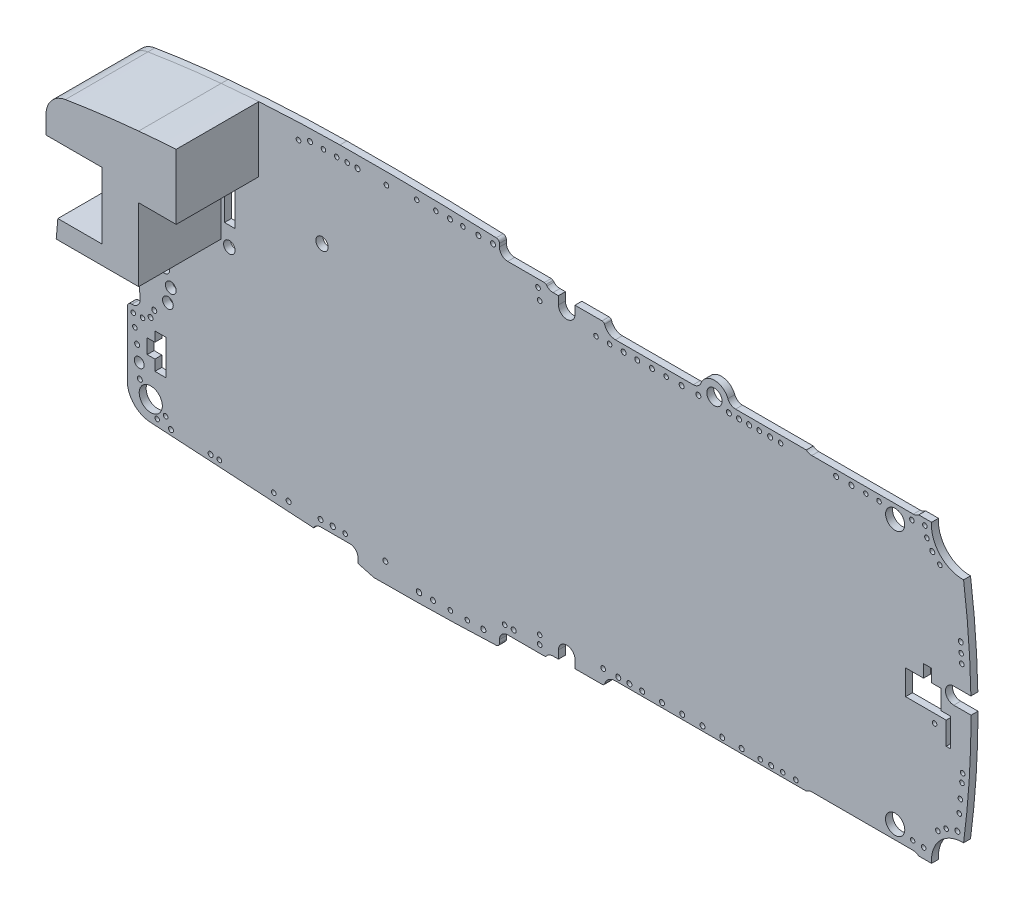
SolidWorks part; units mm, degrees
ref_plane "前视基准面" through (0, 0, 0) normal (0, 0, 1) x (1, 0, 0)
ref_plane "上视基准面" through (0, 0, 0) normal (0, 1, 0) x (1, 0, 0)
ref_plane "右视基准面" through (0, 0, 0) normal (1, 0, 0) x (0, 0, -1)
ref_plane "Dielectric_Layer 图层 1" through (0, 0, 0.84) normal (0, 0, 1) x (1, 0, 0)
sketch "草图1" plane through (0, 0, 0) normal (0, 0, 1) x (1, 0, 0)
  line L0 (-0.5724, -18.938) -> (19.2406, -20.1239)
  line L1 (20.12, -19.6) -> (23.62, -19.6)
  line L2 (24.62, -20.6) -> (24.62, -21.175)
  line L3 (24.62, -21.175) -> (26.5359, -21.6884)
  line L4 (41.75, -20.9855) -> (41.75, -20.6)
  line L5 (42.75, -19.6) -> (47.1862, -19.6)
  line L6 (47.405, -19.5053) -> (47.513, -19.3901)
  line L7 (48.2423, -19.0742) -> (48.9036, -19.0742)
  line L8 (48.9036, -19.0742) -> (48.9034, -18.1002)
  line L9 (50.9034, -18.0998) -> (50.9036, -19.0742)
  line L10 (50.9036, -19.0742) -> (54.2041, -19.0742)
  line L11 (55.8025, -17.9) -> (78.9386, -17.9)
  line L12 (79.6, -17.65) -> (91.9, -17.65)
  line L13 (92.5614, -17.9) -> (94.1119, -17.9)
  line L14 (98.9, 0.05) -> (96.8, 0.05)
  line L15 (96.8, 2.05) -> (98.8801, 2.05)
  line L16 (94.1119, 17.9) -> (92.5614, 17.9)
  line L17 (91.9, 17.65) -> (79.6, 17.65)
  line L18 (78.9386, 17.9) -> (70.3617, 17.9)
  line L19 (65.2383, 17.9) -> (55.8022, 17.9)
  line L20 (54.1774, 19.0746) -> (50.9036, 19.0746)
  line L21 (50.9036, 19.0746) -> (50.9034, 18.0998)
  line L22 (48.9034, 18.1002) -> (48.9036, 19.0742)
  line L23 (48.9036, 19.0742) -> (48.2423, 19.0742)
  line L24 (47.513, 19.3901) -> (47.405, 19.5053)
  line L25 (47.1862, 19.6) -> (42.75, 19.6)
  line L26 (41.75, 20.6) -> (41.75, 20.9798)
  line L27 (-3.1958, 17.0189) -> (-3.1958, 14.7036)
  line L28 (-2.6958, 14.2036) -> (-1.8, 14.2036)
  line L29 (-0.8, 13.2036) -> (-0.8, 7.9919)
  line L30 (-1.742, 7.0519) -> (-2.1738, 2.116)
  line L31 (-2.25, 0.3719) -> (-2.25, -0.3719)
  line L32 (-2.1738, -2.116) -> (-1.7826, -6.5876)
  line L33 (-2.7788, -7.6748) -> (-2.8459, -7.6748)
  line L34 (-3.3459, -8.1748) -> (-3.3461, -15.9932)
  arc A0 (-3.3461, -15.9932) -> (-0.5724, -18.938) centre (-0.3968, -15.9939) ccw
  arc A1 (19.2406, -20.1239) -> (20.12, -19.6) centre (20.1197, -20.5996) cw
  arc A2 (23.62, -19.6) -> (24.62, -20.6) centre (23.62, -20.6) cw
  arc A3 (26.5359, -21.6884) -> (41.3672, -21.3851) centre (27.2689, 305.2421) ccw
  arc A4 (41.3672, -21.3851) -> (41.75, -20.9855) centre (41.3503, -20.9857) ccw
  arc A5 (41.75, -20.6) -> (42.75, -19.6) centre (42.75, -20.6) cw
  arc A6 (47.1862, -19.6) -> (47.405, -19.5053) centre (47.1862, -19.2998) ccw
  arc A7 (47.513, -19.3901) -> (48.2423, -19.0742) centre (48.2427, -20.0748) cw
  arc A8 (48.9034, -18.1002) -> (50.9034, -18.0998) centre (49.9034, -18.1) cw
  arc A9 (54.2041, -19.0742) -> (54.4904, -18.8639) centre (54.2041, -18.7742) ccw
  arc A10 (54.4904, -18.8639) -> (55.8025, -17.9) centre (55.8025, -19.2751) cw
  arc A11 (78.9386, -17.9) -> (79.6, -17.65) centre (79.6001, -18.6502) cw
  arc A12 (91.9, -17.65) -> (92.5614, -17.9) centre (91.8999, -18.6502) cw
  arc A13 (94.1119, -17.9) -> (97.9934, -13.8011) centre (97.9012, -17.6011) cw
  arc A14 (97.9934, -13.8011) -> (98.9, 0.05) centre (-7.2168, 0.0405) ccw
  arc A15 (96.8, 0.05) -> (96.8, 2.05) centre (96.8, 1.05) cw
  arc A16 (98.8801, 2.05) -> (97.9934, 13.8011) centre (-6.6552, -0.0043) ccw
  arc A17 (97.9934, 13.8011) -> (94.1119, 17.9) centre (97.9012, 17.6011) cw
  arc A18 (92.5614, 17.9) -> (91.9, 17.65) centre (91.8999, 18.6502) cw
  arc A19 (79.6, 17.65) -> (78.9386, 17.9) centre (79.6001, 18.6502) cw
  arc A20 (70.3617, 17.9) -> (69.4302, 18.5364) centre (70.3615, 18.8997) cw
  arc A21 (69.4302, 18.5364) -> (66.1698, 18.5364) centre (67.8, 17.9008) ccw
  arc A22 (66.1698, 18.5364) -> (65.2383, 17.9) centre (65.2385, 18.8997) cw
  arc A23 (55.8022, 17.9) -> (54.49, 18.8642) centre (55.8024, 19.2753) cw
  arc A24 (54.49, 18.8642) -> (54.2036, 19.0746) centre (54.2036, 18.7745) ccw
  arc A25 (54.2036, 19.0746) -> (54.1774, 19.0746) centre (54.1905, 18.7861) ccw
  arc A26 (50.9034, 18.0998) -> (48.9034, 18.1002) centre (49.9034, 18.1) cw
  arc A27 (48.2423, 19.0742) -> (47.513, 19.3901) centre (48.2427, 20.0748) cw
  arc A28 (47.405, 19.5053) -> (47.1862, 19.6) centre (47.1862, 19.2998) ccw
  arc A29 (42.75, 19.6) -> (41.75, 20.6) centre (42.75, 20.6) cw
  arc A30 (41.75, 20.9798) -> (41.3657, 21.3795) centre (41.3502, 20.98) ccw
  arc A31 (41.3657, 21.3795) -> (22.4217, 21.6518) centre (26.515, -352.6842) ccw
  arc A32 (22.4217, 21.6518) -> (8.0295, 20.9131) centre (24.2257, -154.0686) ccw
  arc A33 (8.0295, 20.9131) -> (-0.8459, 19.7825) centre (19.7799, -106.7313) ccw
  arc A34 (-0.8459, 19.7825) -> (-3.1958, 17.0189) centre (-0.3944, 17.0177) ccw
  arc A35 (-3.1958, 14.7036) -> (-2.6958, 14.2036) centre (-2.6958, 14.7036) ccw
  arc A36 (-1.8, 14.2036) -> (-0.8, 13.2036) centre (-1.8, 13.2036) cw
  arc A37 (-0.8, 7.9919) -> (-1.742, 7.0519) centre (-1.741, 7.9929) cw
  arc A38 (-2.1738, 2.116) -> (-2.25, 0.3719) centre (17.7613, 0.3713) ccw
  arc A39 (-2.25, -0.3719) -> (-2.1738, -2.116) centre (17.7613, -0.3713) ccw
  arc A40 (-1.7826, -6.5876) -> (-2.7788, -7.6748) centre (-2.7788, -6.6748) cw
  arc A41 (-2.8459, -7.6748) -> (-3.3459, -8.1748) centre (-2.8459, -8.1748) ccw
extrude "Board_Outline 1" add sketch "草图1" along normal blind 0.84 separate body
sketch "草图2" plane through (0, 0, 0) normal (0, 0, 1) x (1, 0, 0)
  line L0 (-0.9394, -12.0264) -> (0, -12.0264)
  line L1 (0, -12.0264) -> (0, -13.3215)
  line L2 (0, -13.3215) -> (1.3401, -13.3215)
  line L3 (1.3401, -13.3215) -> (1.3401, -9.0735)
  line L4 (1.3401, -9.0735) -> (0, -9.0735)
  line L5 (0, -9.0735) -> (0, -10.265)
  line L6 (0, -10.265) -> (-0.9394, -10.265)
  line L7 (-0.9394, -10.265) -> (-0.9394, -12.0264)
extrude "Board_Outline 2" cut sketch "草图2" along normal through all
sketch "草图3" plane through (0, 0, 0) normal (0, 0, 1) x (1, 0, 0)
  line L0 (8.4374, 6.5199) -> (9.7325, 6.5199)
  line L1 (9.7325, 6.5199) -> (9.7325, 12.5812)
  line L2 (9.7325, 12.5812) -> (8.4374, 12.5812)
  line L3 (8.4374, 12.5812) -> (8.4374, 6.5199)
extrude "Board_Outline 3" cut sketch "草图3" along normal through all
sketch "草图4" plane through (0, 0, 0) normal (0, 0, 1) x (1, 0, 0)
  line L0 (90.9633, -1.9761) -> (95.8848, -1.9761)
  line L1 (95.8848, -1.9761) -> (95.8848, -4.7218)
  line L2 (95.8848, -4.7218) -> (96.4028, -4.7218)
  line L3 (96.4028, -4.7218) -> (96.4028, -1.3027)
  line L4 (96.4028, -1.3027) -> (95.2631, -1.3027)
  line L5 (95.2631, -1.3027) -> (95.2631, 1.05)
  line L6 (95.2631, 1.05) -> (94.1119, 1.05)
  line L7 (94.1119, 1.05) -> (94.1119, 2.5827)
  line L8 (94.1119, 2.5827) -> (93.1391, 2.5827)
  line L9 (93.1391, 2.5827) -> (93.1391, 1.05)
  line L10 (93.1391, 1.05) -> (90.9633, 1.05)
  line L11 (90.9633, 1.05) -> (90.9633, -1.9761)
extrude "Board_Outline 4" cut sketch "草图4" along normal through all
sketch "草图5" plane through (0, 0, 0) normal (0, 0, 1) x (1, 0, 0)
  circle A0 centre (-1.9, -13.3375) radius 0.6005
  circle A1 centre (-0.5, -16.5) radius 1.4
  circle A2 centre (0.3, 17.5) radius 1.0966
  circle A3 centre (1.15, -1.8) radius 0.6499
  circle A4 centre (1.2, 1.325) radius 0.6499
  circle A5 centre (1.575, -5.325) radius 0.6499
  circle A6 centre (1.925, -3.575) radius 0.6499
  circle A7 centre (2.5, 3.15) radius 0.6499
  circle A8 centre (9.025, 4.225) radius 0.7
  circle A9 centre (20.25, 10.2) radius 0.75
  circle A10 centre (67.8, 17.9) radius 0.925
  circle A11 centre (89.7, -16) radius 1.1674
  circle A12 centre (89.7, 16) radius 1.156
extrude "NPTH" cut sketch "草图5" along normal through all
sketch "草图6" plane through (0, 0, 0) normal (0, 0, 1) x (1, 0, 0)
  circle A0 centre (-2.625, -8.475) radius 0.275
  circle A1 centre (-2.425, -9.9) radius 0.275
  circle A2 centre (-2.15, -11.55) radius 0.3021
  circle A3 centre (-1.825, -15.05) radius 0.3021
  circle A4 centre (-1.5, -8.45) radius 0.275
  circle A5 centre (-0.525, -7.925) radius 0.3021
  circle A6 centre (-0.15, 16) radius 0.3021
  circle A7 centre (-0.075, -6.95) radius 0.3021
  circle A8 centre (0.275, -18.175) radius 0.275
  circle A9 centre (0.325, 3.425) radius 0.275
  circle A10 centre (1.3, -17.375) radius 0.275
  circle A11 centre (1.95, -18.45) radius 0.3021
  circle A12 centre (3.05, 19.175) radius 0.3021
  circle A13 centre (4.825, 19.325) radius 0.3021
  circle A14 centre (6.475, 19.4) radius 0.3021
  circle A15 centre (6.75, -18.65) radius 0.3021
  circle A16 centre (7.8, -18.7) radius 0.2828
  circle A17 centre (8.025, 19.475) radius 0.275
  circle A18 centre (9.2, 19.6) radius 0.3021
  circle A19 centre (10.825, 19.7) radius 0.3021
  circle A20 centre (14.4, -18.85) radius 0.275
  circle A21 centre (16.2, -18.85) radius 0.3021
  circle A22 centre (17.4, 19.65) radius 0.2828
  circle A23 centre (18.8, 20.2) radius 0.3021
  circle A24 centre (20.075, -18.825) radius 0.3021
  circle A25 centre (20.425, 20.2) radius 0.275
  circle A26 centre (21.55, -18.8) radius 0.3162
  circle A27 centre (22.025, 20.2) radius 0.275
  circle A28 centre (23.05, -18.825) radius 0.275
  circle A29 centre (23.3, 20.25) radius 0.275
  circle A30 centre (24.55, 20.25) radius 0.3148
  circle A31 centre (27.925, -19.275) radius 0.3021
  circle A32 centre (28.05, 20.25) radius 0.2828
  circle A33 centre (31.725, 20.55) radius 0.275
  circle A34 centre (32, -20.5) radius 0.3299
  circle A35 centre (33.7, -20.5) radius 0.3021
  circle A36 centre (34.05, 20.55) radius 0.275
  circle A37 centre (35.75, 20.55) radius 0.3021
  circle A38 centre (35.8, -20.5) radius 0.275
  circle A39 centre (37.325, 20.55) radius 0.275
  circle A40 centre (37.85, -20.5) radius 0.275
  circle A41 centre (39.2, 20.55) radius 0.3
  circle A42 centre (39.8, -20.5) radius 0.3085
  circle A43 centre (40.975, 20.55) radius 0.3021
  circle A44 centre (42.375, -18.725) radius 0.275
  circle A45 centre (43.475, -18.725) radius 0.3021
  circle A46 centre (46.425, 18.7) radius 0.2828
  circle A47 centre (46.625, -18.675) radius 0.275
  circle A48 centre (46.625, -17.65) radius 0.275
  circle A49 centre (46.625, 17.425) radius 0.2828
  circle A50 centre (53.45, 17.1) radius 0.275
  circle A51 centre (54.325, -17.35) radius 0.2881
  circle A52 centre (55.1, 17.1) radius 0.275
  circle A53 centre (56.15, -17.35) radius 0.3021
  circle A54 centre (56.8, 17.1) radius 0.3021
  circle A55 centre (57.5, -17.35) radius 0.3021
  circle A56 centre (58.45, 17.1) radius 0.3021
  circle A57 centre (59.05, -17.35) radius 0.3021
  circle A58 centre (60.225, 17.1) radius 0.3021
  circle A59 centre (61.45, -17.35) radius 0.3021
  circle A60 centre (61.95, 17.1) radius 0.275
  circle A61 centre (63.825, 17.1) radius 0.3021
  circle A62 centre (63.9, -17.35) radius 0.3021
  circle A63 centre (65.85, 17.1) radius 0.3021
  circle A64 centre (66.35, -17.35) radius 0.3021
  circle A65 centre (68.75, -17.35) radius 0.3021
  circle A66 centre (69.55, 17.1) radius 0.3021
  circle A67 centre (70.775, 17.075) radius 0.3021
  circle A68 centre (71.1, -17.35) radius 0.3021
  circle A69 centre (72, 17.075) radius 0.3021
  circle A70 centre (73.225, 17.075) radius 0.2828
  circle A71 centre (73.35, -17.35) radius 0.275
  circle A72 centre (74.55, 17.075) radius 0.3021
  circle A73 centre (74.675, -17.35) radius 0.3021
  circle A74 centre (75.825, 17.075) radius 0.275
  circle A75 centre (76.075, -17.35) radius 0.275
  circle A76 centre (77.675, -17.35) radius 0.2828
  circle A77 centre (82.55, 16.925) radius 0.3021
  circle A78 centre (84.4, 16.925) radius 0.3021
  circle A79 centre (86.15, 16.925) radius 0.2673
  circle A80 centre (87.75, 16.925) radius 0.275
  circle A81 centre (91.725, 16.95) radius 0.275
  circle A82 centre (91.825, -16.625) radius 0.2634
  circle A83 centre (93.15, -16.7) radius 0.275
  circle A84 centre (93.3, 17.15) radius 0.275
  circle A85 centre (93.55, 15.975) radius 0.275
  circle A86 centre (94.2, 14.875) radius 0.3021
  circle A87 centre (94.475, -3.025) radius 0.275
  circle A88 centre (94.875, -14.1) radius 0.275
  circle A89 centre (95.125, 13.95) radius 0.275
  circle A90 centre (95.875, -13.375) radius 0.275
  circle A91 centre (97.25, -12.95) radius 0.3021
  circle A92 centre (97.475, -10.975) radius 0.275
  circle A93 centre (97.6, -9.4) radius 0.275
  circle A94 centre (97.65, 7.125) radius 0.3021
  circle A95 centre (97.7, 5.95) radius 0.275
  circle A96 centre (97.775, 4.875) radius 0.275
  circle A97 centre (97.8, -7.6) radius 0.275
  circle A98 centre (97.875, -6.55) radius 0.275
extrude "PTH" cut sketch "草图6" along normal through all
sketch "草图7" plane through (0, 0, 0) normal (0, 0, 1) x (1, 0, 0)
  line L0 (-3.1958, 14.8826) -> (3.5852, 14.8826)
  line L1 (3.5852, 14.8826) -> (3.5852, 6.8399)
  line L2 (3.5852, 6.8399) -> (-1.7606, 6.8399)
  line L3 (-1.7606, 6.8399) -> (-1.9579, 4.584)
  line L4 (-1.9579, 4.584) -> (8.0295, 4.584)
  line L5 (8.0295, 4.584) -> (8.0295, 13.3916)
  line L6 (8.0295, 13.3916) -> (12.5799, 13.3916)
  line L7 (12.5799, 13.3916) -> (12.5799, 21.2737)
  line L8 (-3.1958, 17.0189) -> (-3.1958, 14.8826)
  arc A0 (12.5799, 21.2737) -> (8.0295, 20.9131) centre (24.0778, -152.7091) ccw
  arc A1 (8.0295, 20.9131) -> (-0.8459, 19.7825) centre (19.7799, -106.7313) ccw
  arc A2 (-0.8459, 19.7825) -> (-3.1958, 17.0189) centre (-0.3944, 17.0177) ccw
extrude "Place_Keepout 零部件外置区域 1" add sketch "草图7" along normal blind 10 from offset 0.84 separate body
